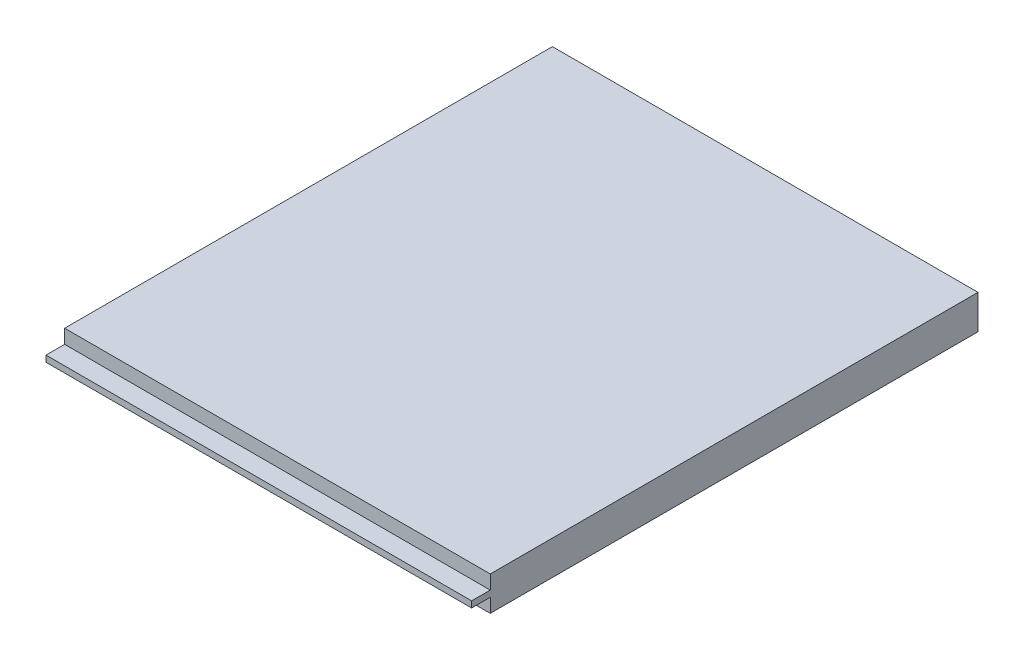
SolidWorks part; units mm, degrees
ref_plane "Front Plane" through (0, 0, 0) normal (0, 0, 1) x (1, 0, 0)
ref_plane "Top Plane" through (0, 0, 0) normal (0, 1, 0) x (1, 0, 0)
ref_plane "Right Plane" through (0, 0, 0) normal (1, 0, 0) x (0, 0, -1)
sketch "Sketch1" plane through (0, 0, 0) normal (0, 0, 1) x (1, 0, 0)
  line L0 (0, 63.3733) -> (0, -132.2399) construction
  line L1 (-34.25, 2.75) -> (34.25, 2.75)
  line L3 (-34.25, -2.75) -> (34.25, -2.75)
  line L5 (-438.1621, 313.5659) -> (438.1621, -313.5659) construction
  line L6 (-236.2003, -169.9757) -> (436.5092, 314.1231) construction
  line L7 (-374.2663, 0) -> (380.8006, 0) construction
  line L8 (-34.25, 2.75) -> (-34.25, -2.75)
  line L9 (34.25, 2.75) -> (34.25, -2.75)
  point P0 (0, 0)
  dimension "D1" = 5.5
  dimension "D2" = 68.5
extrude "Boss-Extrude1" add sketch "Sketch1" along normal mid plane 81.5
sketch "Sketch2" plane through (0, 0, 40.75) normal (0, 0, 1) x (1, 0, 0)
  line L0 (34.25, -2.75) -> (34.25, 2.75) construction
  line L1 (-34.25, 0.5) -> (34.25, 0.5) construction
  line L2 (-34.25, 0.5) -> (-34.25, -0.5) construction
  line L3 (-34.25, -0.5) -> (34.25, -0.5) construction
  line L4 (34.25, 0.5) -> (34.25, -0.5) construction
  line L5 (-34.25, 0.5) -> (34.25, -0.5) construction
  line L6 (-34.25, -0.5) -> (34.25, 0.5) construction
  line L7 (-39.1388, 0) -> (42.4673, 0) construction
  line L9 (-34.25, 2.75) -> (34.25, 2.75)
  line L10 (-34.25, 2.75) -> (-34.25, 0.5)
  line L11 (-34.25, 0.5) -> (34.25, 0.5)
  line L12 (34.25, 2.75) -> (34.25, 0.5)
  line L13 (34.25, -0.5) -> (-34.25, -0.5)
  line L14 (34.25, -0.5) -> (34.25, -2.75)
  line L15 (34.25, -2.75) -> (-34.25, -2.75)
  line L16 (-34.25, -0.5) -> (-34.25, -2.75)
  point P0 (0, 0)
  dimension "D1" = 1
extrude "Cut-Extrude1" cut sketch "Sketch2" against normal blind 3
